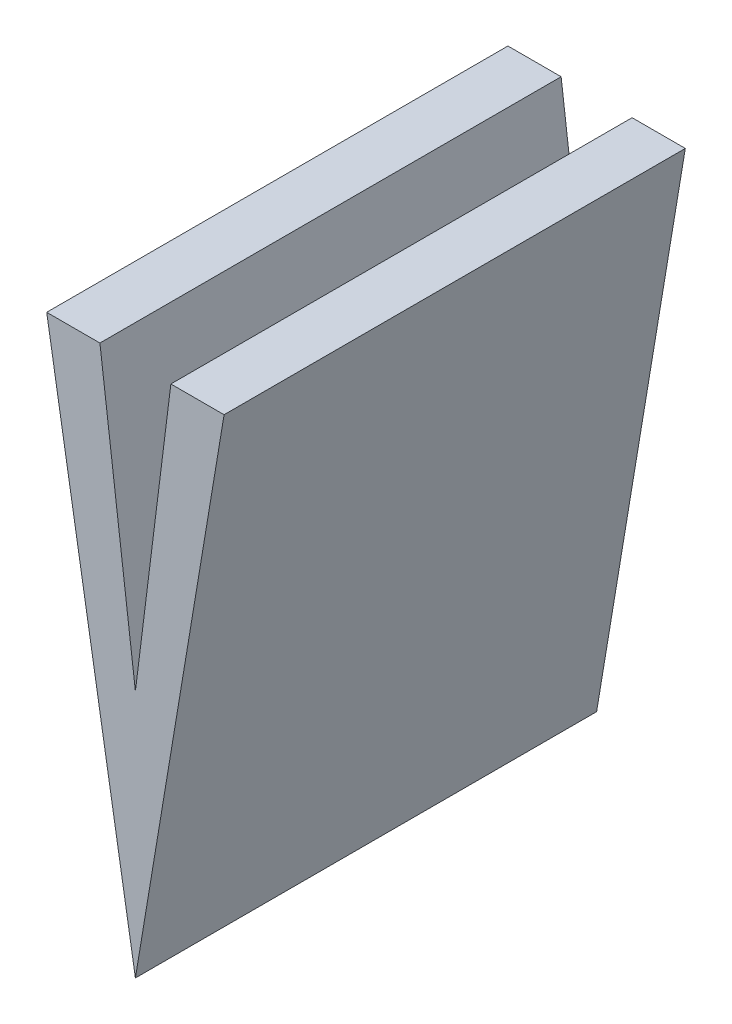
SolidWorks part; units mm, degrees
ref_plane "Front Plane" through (0, 0, 0) normal (0, 0, 1) x (1, 0, 0)
ref_plane "Top Plane" through (0, 0, 0) normal (0, 1, 0) x (1, 0, 0)
ref_plane "Right Plane" through (0, 0, 0) normal (1, 0, 0) x (0, 0, -1)
sketch "Sketch1" plane through (0, 0, 0) normal (0, 0, 1) x (1, 0, 0)
  line L1 (2, 30) -> (5, 30)
  line L2 (5, 30) -> (0, 0)
  line L3 (-2, 30) -> (-5, 30)
  line L4 (-5, 30) -> (0, 0)
  line L5 (0, 30) -> (0, 27)
  line L6 (5, 30) -> (2, 30)
  line L7 (-5, 30) -> (-2, 30)
  line L8 (0, 0) -> (1, 6)
  line L9 (0, 14) -> (-2, 30)
  line L10 (2, 30) -> (0, 14)
  dimension "D1" = 5
  dimension "D2" = 5
  dimension "D3" = 30
  dimension "D4" = 30
  dimension "D5" = 3
  dimension "D6" = 3
  dimension "D7" = 3
  dimension "D8" = 6
extrude "Boss-Extrude1" add sketch "Sketch1" along normal blind 26 contours L1 L10 L9 L3 L4 L2
